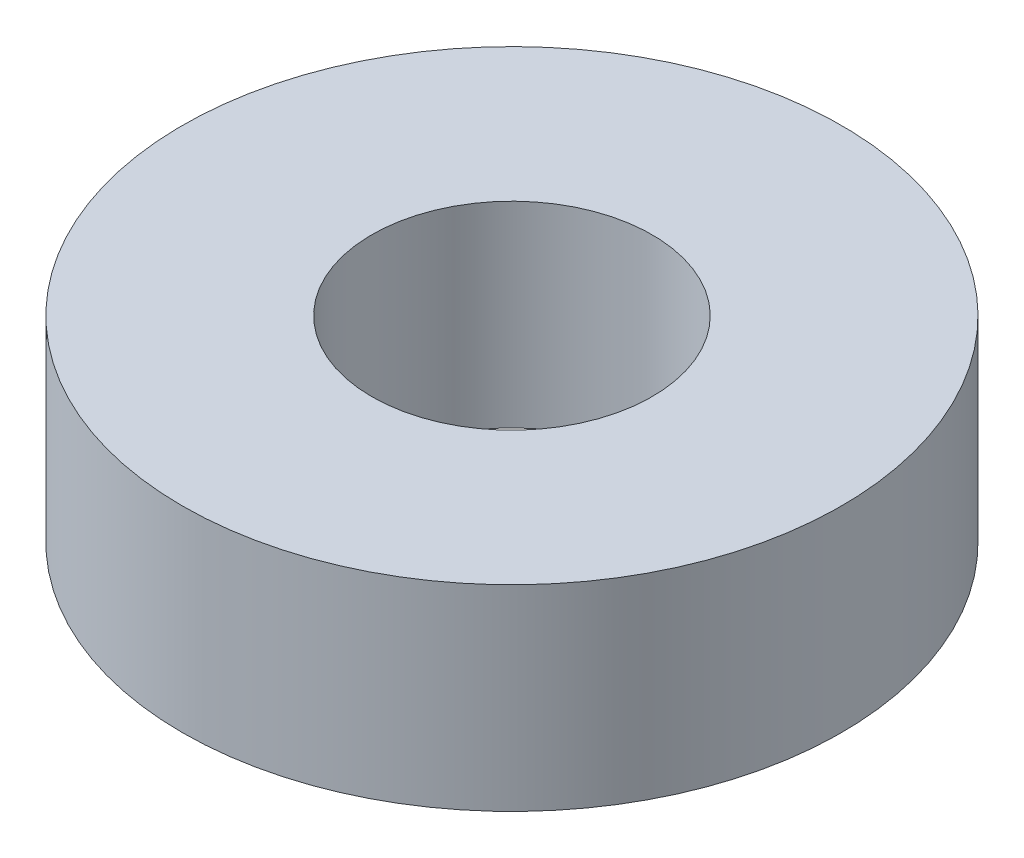
SolidWorks part; units mm, degrees
ref_plane "Front Plane" through (0, 0, 0) normal (0, 0, 1) x (1, 0, 0)
ref_plane "Top Plane" through (0, 0, 0) normal (0, 1, 0) x (1, 0, 0)
ref_plane "Right Plane" through (0, 0, 0) normal (1, 0, 0) x (0, 0, -1)
sketch "Sketch1" plane through (0, 0, 0) normal (0, 1, 0) x (1, 0, 0)
  circle A0 centre (0, 0) radius 23.5
  circle A1 centre (0, 0) radius 10
extrude "Revolved_Equivalent_Extrude" add sketch "Sketch1" along normal blind 14
equation "\"ValveDiameter\" = 50mm"
equation "\"MotorGearTeeth\" = 40"
equation "\"OutputGearTeeth\" = 80"
equation "\"GearModule\" = 1.5mm"
equation "\"PressureAngle\" = 20deg"
equation "\"GearCenterDistance\" = 90mm"
equation "\"GearWidth\" = 18mm"
equation "\"OutputShaftDiameter\" = 20mm"
equation "\"BearingOD\" = 47mm"
equation "\"BearingWidth\" = 14mm"
equation "\"PlateThickness\" = 6mm"
equation "\"ValveRotation\" = 90deg"
